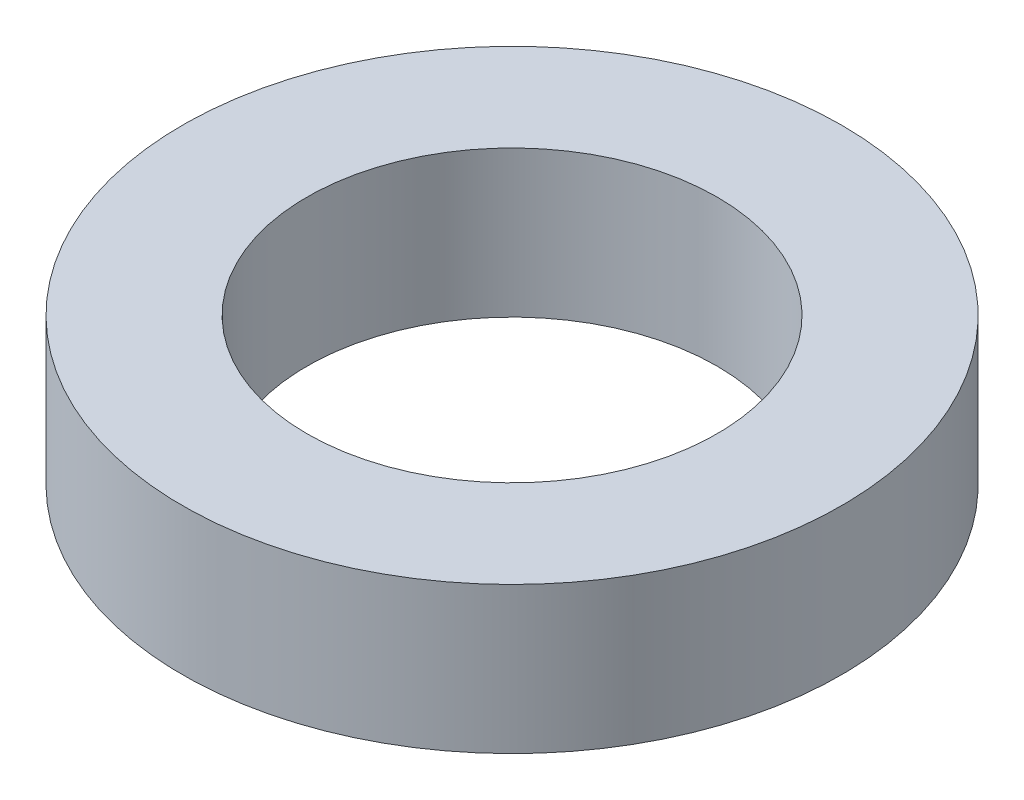
SolidWorks part; units mm, degrees
ref_plane "前视基准面" through (0, 0, 0) normal (0, 0, 1) x (1, 0, 0)
ref_plane "上视基准面" through (0, 0, 0) normal (0, 1, 0) x (1, 0, 0)
ref_plane "右视基准面" through (0, 0, 0) normal (1, 0, 0) x (0, 0, -1)
other "Configuration Table"
sketch "草图1" plane through (0, 0, 0) normal (0, 0, 1) x (1, 0, 0)
  line L0 (0, 0) -> (4.5, 0)
  line L1 (4.5, 0) -> (4.5, 2)
  line L2 (4.5, 2) -> (0, 2)
  line L3 (0, 2) -> (0, 0)
  line L4 (0, 0) -> (0, 2) construction
  dimension "radius" = 4.5
  dimension "height" = 2
revolve "Revolve" add sketch "草图1" angle 360 about L4
sketch "草图2" plane through (0, 2, 0) normal (0, 1, 0) x (1, 0, 0)
  circle A0 centre (0, 0) radius 2.8
  dimension "diameter" = 5.6
extrude "Hole" cut sketch "草图2" against normal through all
